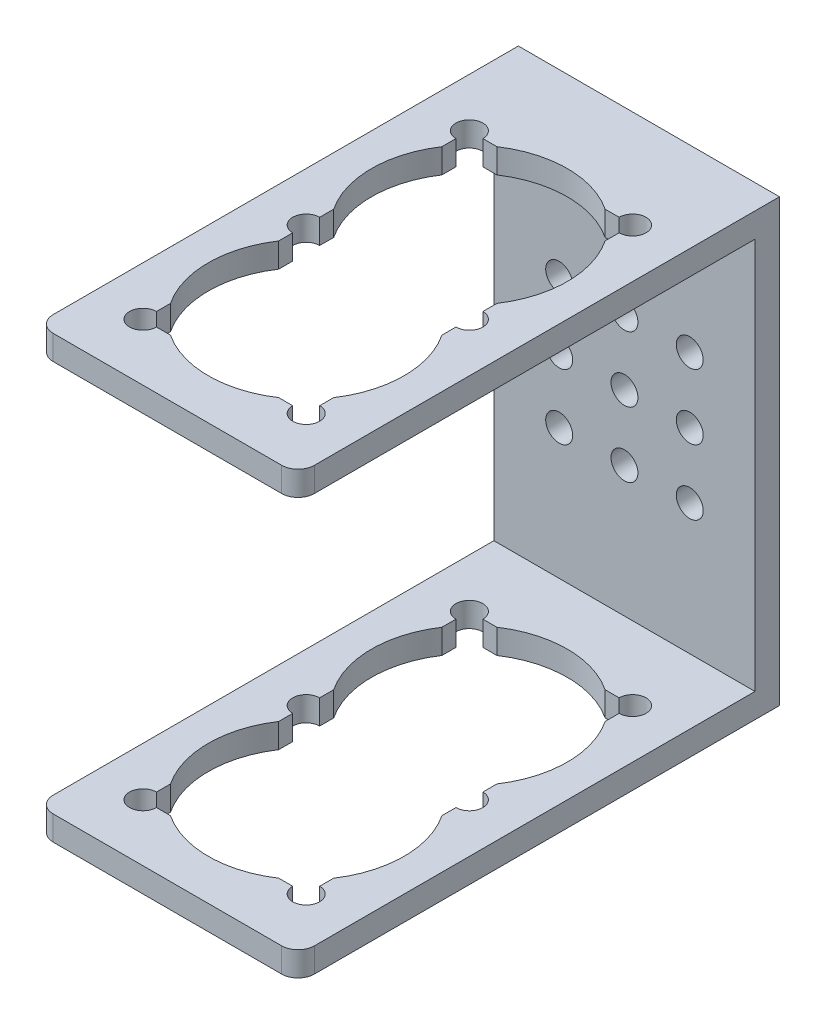
SolidWorks part; units mm, degrees
ref_plane "前视基准面" through (0, 0, 0) normal (0, 0, 1) x (1, 0, 0)
ref_plane "上视基准面" through (0, 0, 0) normal (0, 1, 0) x (1, 0, 0)
ref_plane "右视基准面" through (0, 0, 0) normal (1, 0, 0) x (0, 0, -1)
sketch "草图1" plane through (0, 0, 0) normal (0, 0, 1) x (1, 0, 0)
  line L1 (0, 0) -> (0, 24)
  line L2 (32, 0) -> (32, 24)
  line L5 (16, 12) -> (8, 12)
  line L6 (16, 12) -> (16, 39)
  line L7 (0, 12) -> (0, 39)
  line L8 (16, 39) -> (0, 39)
  line L9 (16, 12) -> (32, 12)
  line L10 (16, 12) -> (16, -15)
  line L11 (32, 12) -> (32, -15)
  line L12 (16, -15) -> (32, -15)
  line L13 (0, 39) -> (32, 39)
  line L14 (0, 39) -> (0, -15)
  line L15 (32, 39) -> (32, -15)
  line L16 (0, -15) -> (32, -15)
  line L17 (16, 12) -> (16, 20)
  line L18 (16, 20) -> (8, 20)
  line L19 (8, 12) -> (8, 20)
  line L20 (16, 12) -> (24, 12)
  line L21 (16, 12) -> (16, 4)
  line L22 (16, 4) -> (24, 4)
  line L23 (24, 12) -> (24, 4)
  line L24 (8, 20) -> (24, 20)
  line L25 (8, 20) -> (8, 4)
  line L26 (8, 4) -> (24, 4)
  line L27 (24, 20) -> (24, 4)
  circle A0 centre (8, 20) radius 1.65
  circle A1 centre (8, 12) radius 1.65
  circle A2 centre (8, 4) radius 1.65
  circle A3 centre (16, 20) radius 1.65
  circle A4 centre (16, 12) radius 1.65
  circle A5 centre (16, 4) radius 1.65
  circle A6 centre (24, 4) radius 1.65
  circle A7 centre (24, 12) radius 1.65
  circle A8 centre (24, 20) radius 1.65
extrude "凸台-拉伸1" add sketch "草图1" along normal blind 3 contours A5 L26 A2 L25 A1 A0 L24 A3 L6 L8 L7 L1 L14 L16 L10 | L24 A8 L27 A7 L9 L2 L15 L13 L6 A3 | L9 A7 L27 A6 L26 A5 L10 L12 L11 L2 | A4 L17 A3 L24 A0 L25 A1 L5 | L27 A8 L24 A3 L17 A4 L20 A7 | A5 L21 A4 L5 A1 L25 A2 L26 | L27 A7 L20 A4 L21 A5 L26 A6
sketch "草图2" plane through (0, 0, 3) normal (0, 0, 1) x (1, 0, 0)
  line L0 (0, 39) -> (32, 39)
  line L1 (0, 39) -> (0, 36)
  line L2 (32, 39) -> (32, 36)
  line L3 (0, 36) -> (32, 36)
  line L4 (32, -15) -> (0, -15)
  line L5 (32, -15) -> (32, -12)
  line L6 (0, -15) -> (0, -12)
  line L7 (32, -12) -> (0, -12)
extrude "凸台-拉伸2" add sketch "草图2" along normal blind 56
sketch "草图3" plane through (0, 39, 0) normal (0, 1, 0) x (1, 0, 0)
  line L0 (0, -59) -> (32, -59)
  line L1 (0, -59) -> (0, -3)
  line L2 (32, -59) -> (32, -3)
  line L3 (0, -3) -> (32, -3)
  line L5 (16, -59) -> (16, -32)
  line L6 (16, -32) -> (16, -3)
  line L8 (16, -32) -> (26, -32)
  line L9 (16, -32) -> (16, -12)
  line L10 (16, -12) -> (26, -12)
  line L11 (26, -32) -> (26, -12)
  line L12 (16, -32) -> (6, -32)
  line L13 (16, -32) -> (16, -52)
  line L14 (16, -52) -> (6, -52)
  line L15 (6, -32) -> (6, -52)
  line L16 (6, -52) -> (26, -52)
  line L17 (6, -52) -> (6, -12)
  line L18 (6, -12) -> (26, -12)
  line L19 (26, -52) -> (26, -12)
  circle A0 centre (6, -52) radius 1.65
  circle A1 centre (6, -32) radius 1.65
  circle A2 centre (6, -12) radius 1.65
  circle A3 centre (26, -12) radius 1.65
  circle A4 centre (26, -52) radius 1.65
  circle A5 centre (26, -32) radius 1.65
  circle A6 centre (16, -42) radius 12
  circle A7 centre (16, -22) radius 12
extrude "切除-拉伸2" cut sketch "草图3" against normal blind 58 contours L17 A0 L16 | L16 A0 L17 | L17 A1 L15 | L15 A1 L12 | L12 A1 L17 | A6 L12 A1 L17 | A7 L17 A1 L12 | A6 L17 A0 L16 | A6 L16 A4 L19 | L19 A4 L16 | L16 A4 L19 | A6 L19 A5 L8 | L8 A5 L19 | A7 L8 A5 L19 | L11 A5 L8 | L19 A5 L11 | A7 L19 A3 L18 | L18 A3 L19 | L19 A3 L18 | A7 L18 A2 L17 | L17 A2 L18 | L18 A2 L17
fillet "圆角1" radius 2 4 edges at (32, 37.5, 59) (0, 37.5, 59) (32, -13.5, 59) (0, -13.5, 59)
